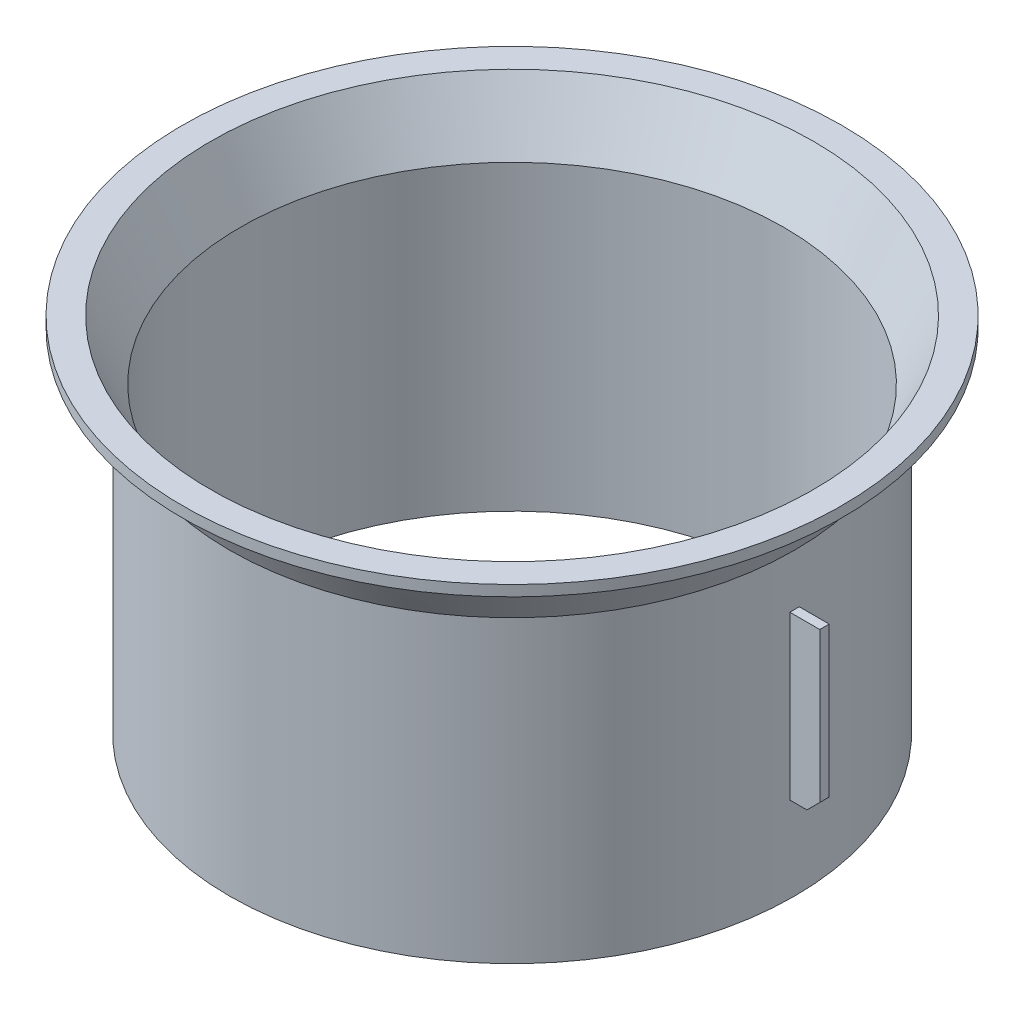
SolidWorks part; units mm, degrees
ref_plane "Front" through (0, 0, 0) normal (0, 0, 1) x (1, 0, 0)
ref_plane "Top" through (0, 0, 0) normal (0, 1, 0) x (1, 0, 0)
ref_plane "Right" through (0, 0, 0) normal (1, 0, 0) x (0, 0, -1)
sketch "Esquisse1" plane through (0, 0, 0) normal (0, 0, 1) x (1, 0, 0)
  line L0 (33, 0) -> (33, 35)
  line L1 (33, 35) -> (36, 41)
  line L2 (36, 41) -> (38.5, 41)
  line L3 (38.5, 41) -> (38.5, 42.25)
  line L4 (38.5, 42.25) -> (35.2275, 42.25)
  line L5 (35.2275, 42.25) -> (31.75, 35.2951)
  line L6 (31.75, 35.2951) -> (31.75, 0)
  line L7 (31.75, 0) -> (33, 0)
  line L8 (0, 0) -> (0, 46.75) construction
  dimension "D1" = 66
  dimension "D2" = 1.25
  dimension "D3" = 1.25
  dimension "D4" = 1.25
  dimension "D5" = 35
  dimension "D6" = 6
  dimension "D7" = 77
  dimension "D8" = 2.5
revolve "Révolution1" add sketch "Esquisse1" angle 360 about L8
sketch "Esquisse2" plane through (0, 0, 0) normal (0, -1, 0) x (1, 0, 0)
  line L0 (0, 0) -> (-33, 0) construction
  line L1 (-32.9954, 0.55) -> (-36.4954, 0.55)
  line L2 (-36.4954, -0.55) -> (-36.4954, 0.55)
  line L3 (-32.9954, 0.55) -> (-32.4954, 0)
  line L4 (-32.9954, -0.55) -> (-32.4954, 0)
  line L5 (0, 0) -> (0, 9.7933) construction
  line L6 (-32.9954, -0.55) -> (-36.4954, -0.55)
  line L7 (32.9954, -0.55) -> (36.4954, -0.55)
  line L8 (32.9954, -0.55) -> (32.4954, 0)
  line L9 (32.9954, 0.55) -> (32.4954, 0)
  line L10 (36.4954, -0.55) -> (36.4954, 0.55)
  line L11 (32.9954, 0.55) -> (36.4954, 0.55)
  circle A0 centre (0, 0) radius 33 construction
  dimension "D1" = 1.1
  dimension "D2" = 3.5
  dimension "D3" = 0.5
extrude "Boss.-Extru.1" add sketch "Esquisse2" against normal blind 19 from offset 10 offset against normal yes
chamfer "Chanfrein1" distance 1.5 angle 45 2 edges at (36.4954, 10, 0) (-36.4954, 10, 0)
